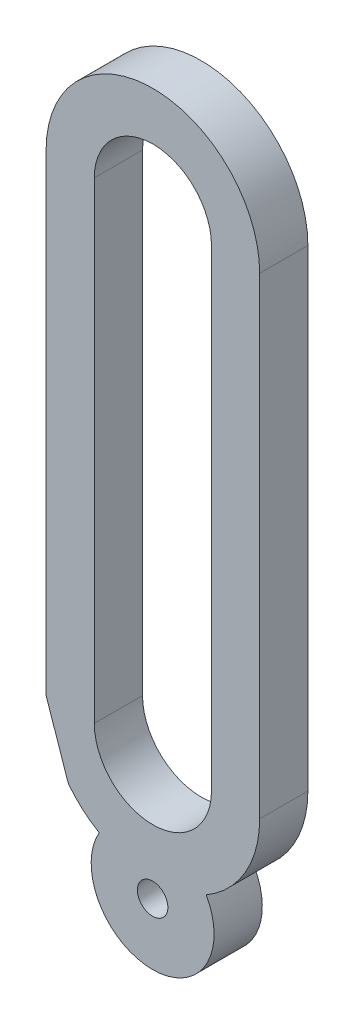
SolidWorks part; units mm, degrees
ref_plane "Piano frontale" through (0, 0, 0) normal (0, 0, 1) x (1, 0, 0)
ref_plane "Piano superiore" through (0, 0, 0) normal (0, 1, 0) x (1, 0, 0)
ref_plane "Piano destro" through (0, 0, 0) normal (1, 0, 0) x (0, 0, -1)
sketch "Schizzo1" plane through (0, 0, 0) normal (0, 0, 1) x (1, 0, 0)
  line L0 (0, -48.9995) -> (0, 48.9995) construction
  line L1 (-12.1501, -48.9995) -> (-12.1501, 48.9995)
  line L2 (12.1501, -48.9995) -> (12.1501, 48.9995)
  arc A0 (-12.1501, -48.9995) -> (12.1501, -48.9995) centre (0, -48.9995) ccw
  arc A1 (12.1501, 48.9995) -> (-12.1501, 48.9995) centre (0, 48.9995) ccw
  point P2 (0, 0)
extrude "Estrusione-Sottile1" add sketch "Schizzo1" along normal blind 10 thin thin type one direction wall 10
sketch "Schizzo2" plane through (0, 0, 10) normal (0, 0, 1) x (1, 0, 0)
  line L0 (-22.1501, -48.9995) -> (-17.5309, -62.5381)
  line L1 (-22.1501, -48.9995) -> (-24.8758, -48.9995)
  line L2 (-24.8758, -48.9995) -> (-24.8758, -62.5381)
  line L3 (-24.8758, -62.5381) -> (-17.5309, -62.5381)
  arc A0 (-22.1501, -48.9995) -> (22.1501, -48.9995) centre (0, -48.9995) ccw construction
extrude "Taglio-Estrusione2" cut sketch "Schizzo2" against normal blind 10
sketch "Schizzo3" plane through (0, 0, 10) normal (0, 0, 1) x (1, 0, 0)
  circle A1 centre (-0.0586, -74.4471) radius 12.75
  circle A2 centre (-0.0586, -74.4471) radius 3.1616
  point P3 (-0.0586, -74.4471)
extrude "Estrusione-Estrusione1" add sketch "Schizzo3" against normal blind 10
sketch "Schizzo8" plane through (0, 0, 10) normal (0, 0, 1) x (1, 0, 0)
  line L0 (0, 71.1496) -> (0, -61.1496) construction
  arc A1 (22.1501, 48.9995) -> (-22.1501, 48.9995) centre (0, 48.9995) ccw construction
  arc A2 (-12.1501, -48.9995) -> (12.1501, -48.9995) centre (0, -48.9995) ccw construction
equation "\"80ù\"=90"
